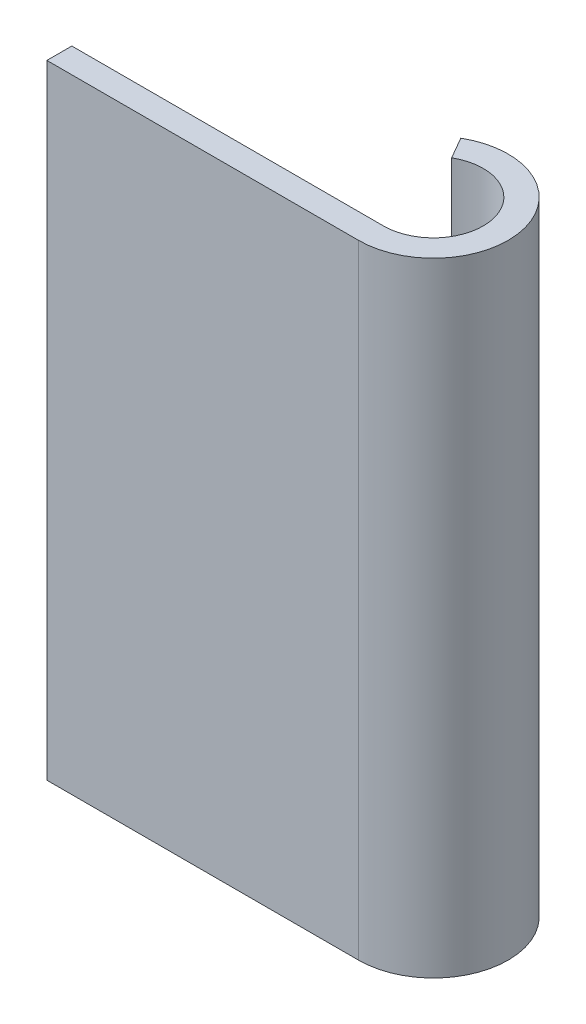
SolidWorks part; units mm, degrees
ref_plane "Front Plane" through (0, 0, 0) normal (0, 0, 1) x (1, 0, 0)
ref_plane "Top Plane" through (0, 0, 0) normal (0, 1, 0) x (1, 0, 0)
ref_plane "Right Plane" through (0, 0, 0) normal (1, 0, 0) x (0, 0, -1)
sketch "Sketch1" plane through (0, 0, 0) normal (0, 1, 0) x (1, 0, 0)
  line L0 (0, -3.2) -> (-20, -3.2)
  line L1 (-20, -3.2) -> (-20, -4.8)
  line L2 (-20, -4.8) -> (0, -4.8)
  line L3 (-2.4, 4.1569) -> (-1.6, 2.7713)
  arc A0 (-1.6, 2.7713) -> (0, -3.2) centre (0, 0) cw
  arc A1 (-2.4, 4.1569) -> (0, -4.8) centre (0, 0) cw
  dimension "D1" = 3.2
  dimension "D2" = 20
  dimension "D3" = 1.6
  dimension "D4" = 60
extrude "Boss-Extrude1" add sketch "Sketch1" along normal blind 40
